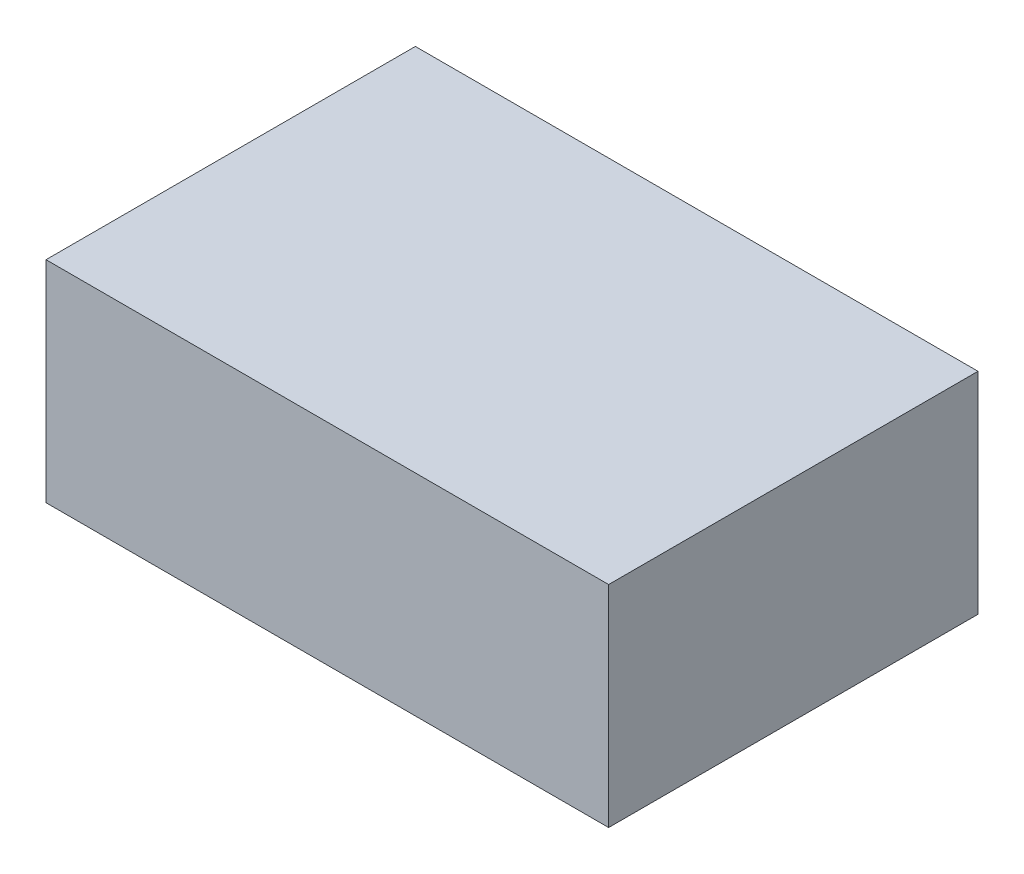
SolidWorks part; units mm, degrees
ref_plane "Front" through (0, 0, 0) normal (0, 0, 1) x (1, 0, 0)
ref_plane "Top" through (0, 0, 0) normal (0, 1, 0) x (1, 0, 0)
ref_plane "Right" through (0, 0, 0) normal (1, 0, 0) x (0, 0, -1)
sketch "Sketch1" plane through (0, 0, 0) normal (0, 1, 0) x (1, 0, 0)
  line L1 (-13.716, -9.0043) -> (13.716, -9.0043)
  line L2 (-13.716, -9.0043) -> (-13.716, 9.0043)
  line L3 (-13.716, 9.0043) -> (13.716, 9.0043)
  line L4 (13.716, -9.0043) -> (13.716, 9.0043)
  line L5 (-13.716, -9.0043) -> (13.716, 9.0043) construction
  line L6 (-13.716, 9.0043) -> (13.716, -9.0043) construction
  point P0 (0, 0)
  dimension "D1" = 18.0086
  dimension "D2" = 27.432
extrude "Boss-Extrude1" add sketch "Sketch1" along normal blind 10.2616
sketch "Sketch2" plane through (0, 0, 0) normal (0, -1, 0) x (1, 0, 0)
  line L0 (0, 9.0043) -> (0, -9.0043) construction
  line L1 (-13.716, 9.0043) -> (13.716, 9.0043) construction
  line L2 (13.716, -9.0043) -> (-13.716, -9.0043) construction
  line L3 (-13.716, 0) -> (13.716, 0) construction
  line L4 (-13.716, -9.0043) -> (-13.716, 9.0043) construction
  line L5 (13.716, 9.0043) -> (13.716, -9.0043) construction
  line L6 (-0.5969, 0.5969) -> (-0.5969, 1.9685)
  line L7 (-0.5969, 1.9685) -> (0.5969, 1.9685)
  line L8 (0.5969, 1.9685) -> (0.5969, 0.5969)
  line L9 (0.5969, 0.5969) -> (1.9685, 0.5969)
  line L10 (1.9685, 0.5969) -> (1.9685, -0.5969)
  line L11 (1.9685, -0.5969) -> (0.5969, -0.5969)
  line L12 (0.5969, -0.5969) -> (0.5969, -1.9685)
  line L13 (0.5969, -1.9685) -> (-0.5969, -1.9685)
  line L14 (-0.5969, -1.9685) -> (-0.5969, -0.5969)
  line L15 (-0.5969, -0.5969) -> (-1.9685, -0.5969)
  line L16 (-1.9685, -0.5969) -> (-1.9685, 0.5969)
  line L17 (-1.9685, 0.5969) -> (-0.5969, 0.5969)
  dimension "D1" = 1.3716
  dimension "D2" = 1.1938
extrude "Cut-Extrude1" cut sketch "Sketch2" against normal blind 5.08 contours L9 L10 L11 L12 L13 L14 L15 L16 L17 L6 L7 L8
